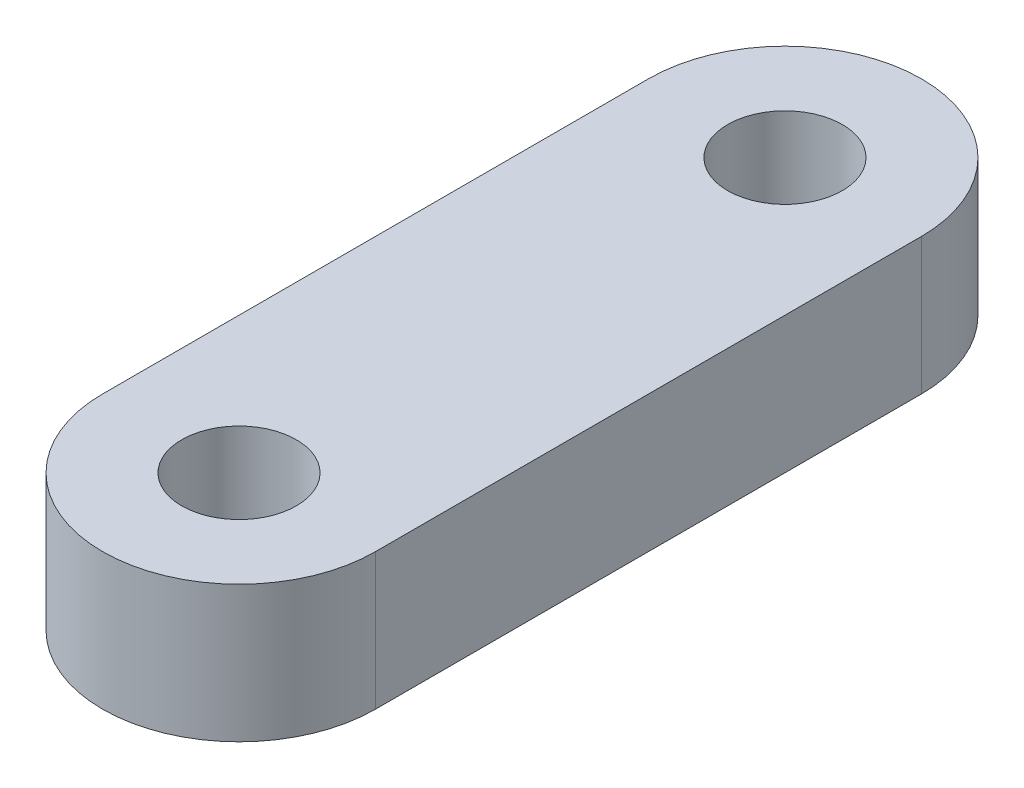
SolidWorks part; units mm, degrees
material "5052-H34"
ref_plane "正面" through (0, 0, 0) normal (0, 0, 1) x (1, 0, 0)
ref_plane "平面" through (0, 0, 0) normal (0, 1, 0) x (1, 0, 0)
ref_plane "右側面" through (0, 0, 0) normal (1, 0, 0) x (0, 0, -1)
sketch "ｽｹｯﾁ1" plane through (0, 0, 0) normal (0, 1, 0) x (1, 0, 0)
  line L0 (0, -10) -> (0, 10) construction
  line L1 (-5, -10) -> (-5, 10)
  line L2 (5, -10) -> (5, 10)
  arc A0 (-5, -10) -> (5, -10) centre (0, -10) ccw
  arc A1 (5, 10) -> (-5, 10) centre (0, 10) ccw
  circle A2 centre (0, 10) radius 2.1
  circle A3 centre (0, -10) radius 2.1
  point P2 (0, 0)
  dimension "D2" = 5
  dimension "D3" = 4.2
  dimension "D1" = 20
extrude "ﾎﾞｽ - 押し出し1" add sketch "ｽｹｯﾁ1" along normal blind 5
